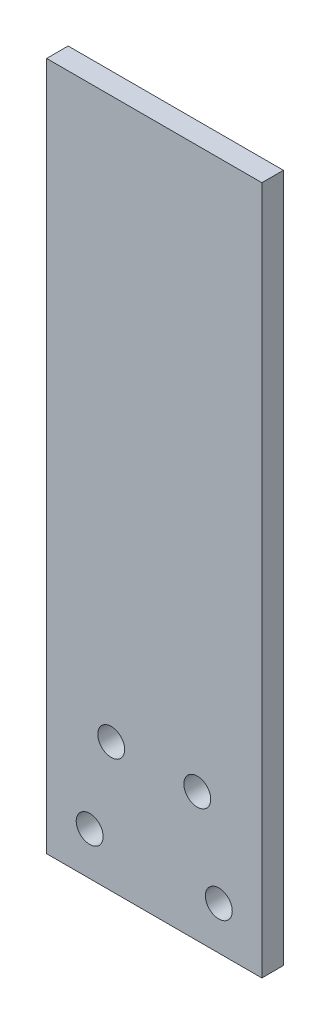
SolidWorks part; units mm, degrees
material "6061-T6 (SS)"
ref_plane "Front Plane" through (0, 0, 0) normal (0, 0, 1) x (1, 0, 0)
ref_plane "Top Plane" through (0, 0, 0) normal (0, 1, 0) x (1, 0, 0)
ref_plane "Right Plane" through (0, 0, 0) normal (1, 0, 0) x (0, 0, -1)
sketch "Sketch2" plane through (0, 0, 0) normal (0, 0, 1) x (1, 0, 0)
  line L1 (-31.75, -101.6) -> (31.75, -101.6)
  line L2 (-31.75, -101.6) -> (-31.75, 101.6)
  line L3 (-31.75, 101.6) -> (31.75, 101.6)
  line L4 (31.75, -101.6) -> (31.75, 101.6)
  line L5 (-31.75, -101.6) -> (31.75, 101.6) construction
  line L6 (-31.75, 101.6) -> (31.75, -101.6) construction
  point P0 (0, 0)
  dimension "D1" = 203.2
  dimension "D2" = 63.5
extrude "Boss-Extrude1" add sketch "Sketch2" along normal mid plane 6.35 contours L2 L3 L4 L1
hole_wizard "Tap Drill for 3/8-16 Tap1" positions "Sketch3" profile "Sketch4" hole size "3/8-16" standard "ANSI Inch" end condition through all
sketch "Sketch3" plane through (0, 0, 3.175) normal (0, 0, 1) x (1, 0, 0)
  line L1 (-12.7, -63.5) -> (12.7, -63.5) construction
  line L3 (-19.05, -88.9) -> (19.05, -88.9) construction
  line L5 (-31.75, -101.6) -> (31.75, -101.6) construction
  point P23 (-12.7, -63.5)
  point P24 (12.7, -63.5)
  point P27 (-19.05, -88.9)
  point P28 (19.05, -88.9)
  point P32 (0, -101.6)
  point P33 (0, -88.9)
  point P34 (0, -63.5)
  dimension "D1" = 25.4
  dimension "D2" = 38.1
  dimension "D3" = 38.1
  dimension "D4" = 12.7
sketch "Sketch4" plane through (-12.7, -63.5, 3.175) normal (1, 0, 0) x (0, -1, 0)
  line L0 (0, 0) -> (0, 6.35)
  line L1 (0, 6.35) -> (3.9687, 6.35)
  line L2 (3.9687, 6.35) -> (3.9687, 0)
  line L5 (3.9687, 0) -> (0, 0)
  line L11 (0, -6.35) -> (0, 107.95) construction
  dimension "Thru Hole Dia." = 7.9375
  dimension "Thru Hole Depth" = 6.35
